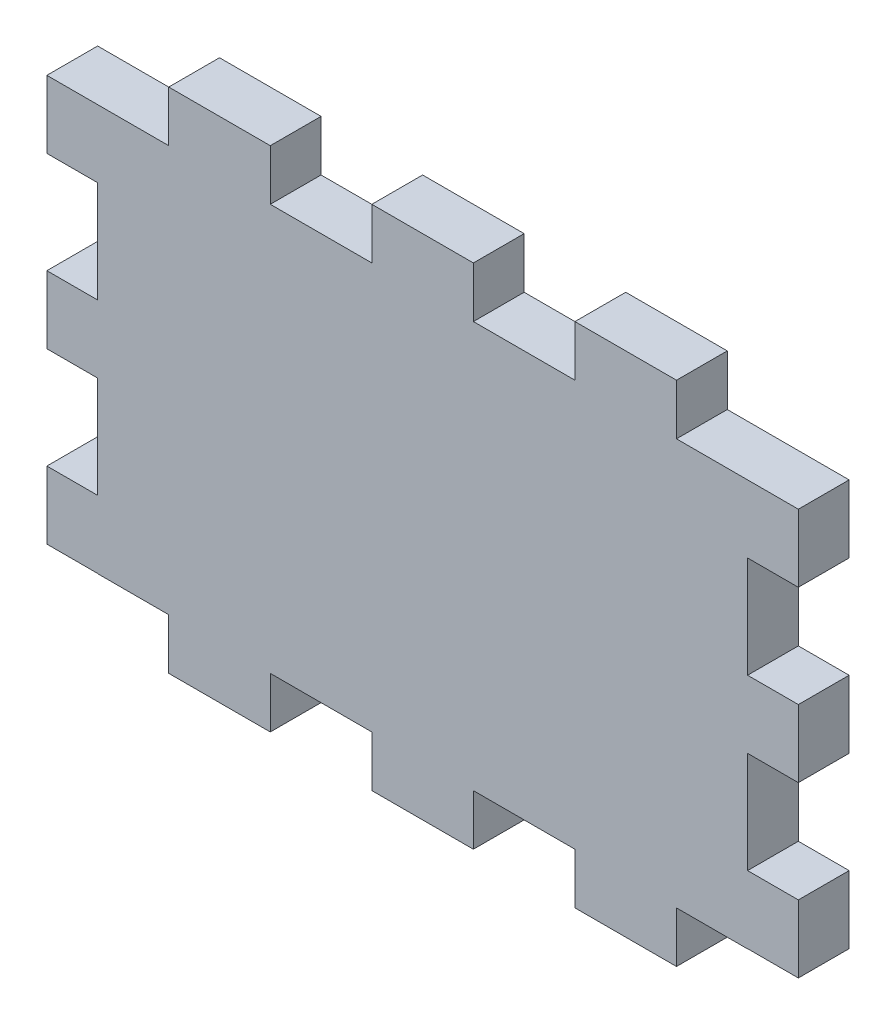
SolidWorks part; units mm, degrees
material "Beech"
ref_plane "Front" through (0, 0, 0) normal (0, 0, 1) x (1, 0, 0)
ref_plane "Top" through (0, 0, 0) normal (0, 1, 0) x (1, 0, 0)
ref_plane "Right" through (0, 0, 0) normal (1, 0, 0) x (0, 0, -1)
sketch "Sketch1" plane through (0, 0, 0) normal (0, 0, 1) x (1, 0, 0)
  line L0 (-2.5, -10) -> (-2.5, -12.5)
  line L1 (-18.5, -10) -> (18.5, -10)
  line L2 (-18.5, -10) -> (-18.5, 10) construction
  line L3 (-18.5, 10) -> (18.5, 10)
  line L4 (18.5, -10) -> (18.5, 10) construction
  line L5 (-18.5, -10) -> (18.5, 10) construction
  line L6 (-18.5, 10) -> (18.5, -10) construction
  line L7 (7.5, 10) -> (12.5, 10)
  line L8 (7.5, 10) -> (7.5, 12.5)
  line L9 (7.5, 12.5) -> (12.5, 12.5)
  line L10 (12.5, 10) -> (12.5, 12.5)
  line L11 (7.5, 10) -> (12.5, 12.5) construction
  line L12 (7.5, 12.5) -> (12.5, 10) construction
  line L13 (7.5, -10) -> (12.5, -10)
  line L14 (7.5, -10) -> (7.5, -12.5)
  line L15 (7.5, -12.5) -> (12.5, -12.5)
  line L16 (12.5, -10) -> (12.5, -12.5)
  line L17 (7.5, -10) -> (12.5, -12.5) construction
  line L18 (7.5, -12.5) -> (12.5, -10) construction
  line L19 (-2.5, -10) -> (2.5, -10)
  line L20 (2.5, -10) -> (2.5, -12.5)
  line L21 (-2.5, -12.5) -> (2.5, -12.5)
  line L22 (-12.5, -10) -> (-12.5, -12.5)
  line L23 (-12.5, -10) -> (-7.5, -10)
  line L24 (-7.5, -10) -> (-7.5, -12.5)
  line L25 (-12.5, -12.5) -> (-7.5, -12.5)
  line L30 (-2.5, 10) -> (-2.5, 12.5)
  line L31 (-2.5, 10) -> (2.5, 10)
  line L32 (2.5, 10) -> (2.5, 12.5)
  line L33 (-2.5, 12.5) -> (2.5, 12.5)
  line L34 (-12.5, 10) -> (-12.5, 12.5)
  line L35 (-12.5, 10) -> (-7.5, 10)
  line L36 (-7.5, 10) -> (-7.5, 12.5)
  line L37 (-12.5, 12.5) -> (-7.5, 12.5)
  line L42 (-22.5, 10) -> (-22.5, 12.5) [skipped]
  line L43 (-22.5, 12.5) -> (-17.5, 12.5) [skipped]
  line L44 (-17.5, 10) -> (-17.5, 12.5) [skipped]
  line L45 (-22.5, 10) -> (-17.5, 10) [skipped]
  line L46 (-22.5, -10) -> (-22.5, -12.5) [skipped]
  line L47 (-22.5, -12.5) -> (-17.5, -12.5) [skipped]
  line L48 (-17.5, -10) -> (-17.5, -12.5) [skipped]
  line L49 (-22.5, -10) -> (-17.5, -10) [skipped]
  line L50 (-18.5, 10) -> (-18.5, 6.67)
  line L51 (-18.5, 6.67) -> (-16, 6.67)
  line L52 (-16, 6.67) -> (-16, 1.67)
  line L53 (-16, 1.67) -> (-18.5, 1.67)
  line L54 (-16, -1.66) -> (-16, -6.66)
  line L55 (-18.5, -1.66) -> (-16, -1.66)
  line L56 (-18.5, 1.67) -> (-18.5, -1.66)
  line L57 (-16, -6.66) -> (-18.5, -6.66)
  line L58 (-16, -9.99) -> (-16, -14.99)
  line L59 (-18.5, -9.99) -> (-16, -9.99)
  line L60 (-18.5, -6.66) -> (-18.5, -9.99)
  line L61 (-16, -14.99) -> (-18.5, -14.99)
  line L62 (-18.5, -14.99) -> (-18.5, -10)
  line L63 (0, 3.4262) -> (0, -2.5) construction
  line L64 (18.5, -14.99) -> (18.5, -10)
  line L65 (16, -14.99) -> (18.5, -14.99)
  line L66 (18.5, -6.66) -> (18.5, -9.99)
  line L67 (18.5, -9.99) -> (16, -9.99)
  line L68 (16, -9.99) -> (16, -14.99)
  line L69 (16, -6.66) -> (18.5, -6.66)
  line L70 (18.5, 1.67) -> (18.5, -1.66)
  line L71 (18.5, -1.66) -> (16, -1.66)
  line L72 (16, -1.66) -> (16, -6.66)
  line L73 (16, 1.67) -> (18.5, 1.67)
  line L74 (16, 6.67) -> (16, 1.67)
  line L75 (18.5, 6.67) -> (16, 6.67)
  line L76 (18.5, 10) -> (18.5, 6.67)
  point P0 (0, 0)
  point P10 (10, 11.25)
  point P16 (10, -11.25)
  dimension "D1" = 20
  dimension "D2" = 37
  dimension "D3" = 6
  dimension "D4" = 2.5
  dimension "D5" = 5
  dimension "D6" = 6
  dimension "D7" = 5
  dimension "D8" = 2.5
  dimension "D11" = 5
  dimension "D12" = 5
  dimension "D13" = 3.33
  dimension "D14" = 5
  dimension "D15" = 2.5
  dimension "D9" = 4
  dimension "D10" = 4
  dimension "D16" = 3
extrude "Boss-Extrude1" add sketch "Sketch1" along normal blind 2.5
